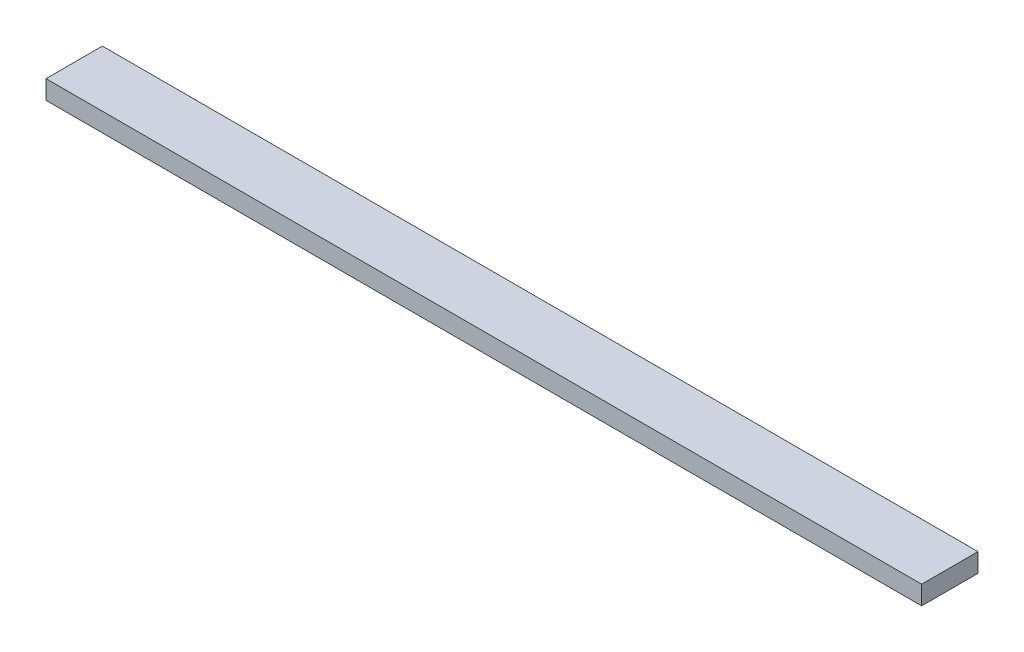
SolidWorks part; units mm, degrees
material "Pine"
ref_plane "Front Plane" through (0, 0, 0) normal (0, 0, 1) x (1, 0, 0)
ref_plane "Top Plane" through (0, 0, 0) normal (0, 1, 0) x (1, 0, 0)
ref_plane "Right Plane" through (0, 0, 0) normal (1, 0, 0) x (0, 0, -1)
sketch "Sketch1" plane through (0, 0, 0) normal (0, 1, 0) x (1, 0, 0)
  line L0 (0, 75) -> (2330, 75) construction
  line L1 (0, 0) -> (2330, 0)
  line L2 (0, 0) -> (0, 150)
  line L3 (0, 150) -> (2330, 150)
  line L4 (2330, 0) -> (2330, 150)
  dimension "D1" = 150
  dimension "D2" = 2330
extrude "Boss-Extrude1" add sketch "Sketch1" along normal blind 50
